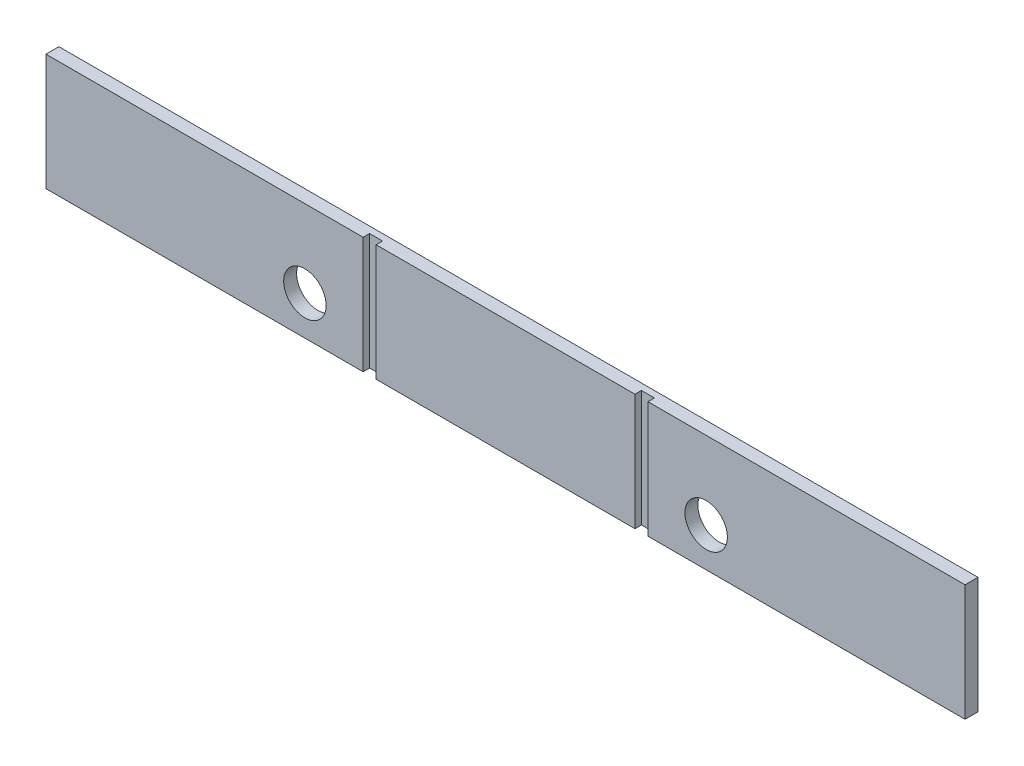
SolidWorks part; units mm, degrees
ref_plane "Front Plane" through (0, 0, 0) normal (0, 0, 1) x (1, 0, 0)
ref_plane "Top Plane" through (0, 0, 0) normal (0, 1, 0) x (1, 0, 0)
ref_plane "Right Plane" through (0, 0, 0) normal (1, 0, 0) x (0, 0, -1)
sketch "Sketch1" plane through (0, 0, 0) normal (0, 0, 1) x (1, 0, 0)
  line L1 (0, 0) -> (901.7, 0)
  line L2 (0, 0) -> (0, 114.3)
  line L3 (0, 114.3) -> (901.7, 114.3)
  line L4 (901.7, 0) -> (901.7, 114.3)
  dimension "D1" = 901.7
  dimension "D2" = 114.3
extrude "Boss-Extrude1" add sketch "Sketch1" along normal blind 12.7
sketch "Sketch2" plane through (0, 0, 12.7) normal (0, 0, 1) x (1, 0, 0)
  line L0 (901.7, 114.3) -> (0, 114.3) construction
  line L1 (311.15, 114.3) -> (323.85, 114.3)
  line L2 (311.15, 114.3) -> (311.15, 0)
  line L3 (311.15, 0) -> (323.85, 0)
  line L4 (323.85, 114.3) -> (323.85, 0)
  line L5 (0, 0) -> (901.7, 0) construction
  line L6 (0, 114.3) -> (0, 0) construction
  line L7 (901.7, 0) -> (901.7, 114.3) construction
  line L8 (577.85, 114.3) -> (590.55, 114.3)
  line L9 (577.85, 114.3) -> (577.85, 0)
  line L10 (577.85, 0) -> (590.55, 0)
  line L11 (590.55, 114.3) -> (590.55, 0)
  dimension "D1" = 12.7
  dimension "D2" = 311.15
  dimension "D3" = 12.7
  dimension "D4" = 311.15
extrude "Cut-Extrude1" cut sketch "Sketch2" against normal blind 6.35
sketch "Sketch3" plane through (0, 0, 0) normal (0, 0, -1) x (-1, 0, 0)
  line L0 (0, 0) -> (-901.7, 0) construction
  line L1 (-901.7, 0) -> (-901.7, 114.3) construction
  line L2 (-450.85, 114.3) -> (-450.85, 0) construction
  line L3 (-901.7, 114.3) -> (0, 114.3) construction
  circle A0 centre (-647.7, 38.1) radius 20.828
  circle A1 centre (-254, 38.1) radius 20.828
  dimension "D1" = 41.656
  dimension "D2" = 38.1
  dimension "D3" = 254
extrude "Cut-Extrude2" cut sketch "Sketch3" against normal up to next
